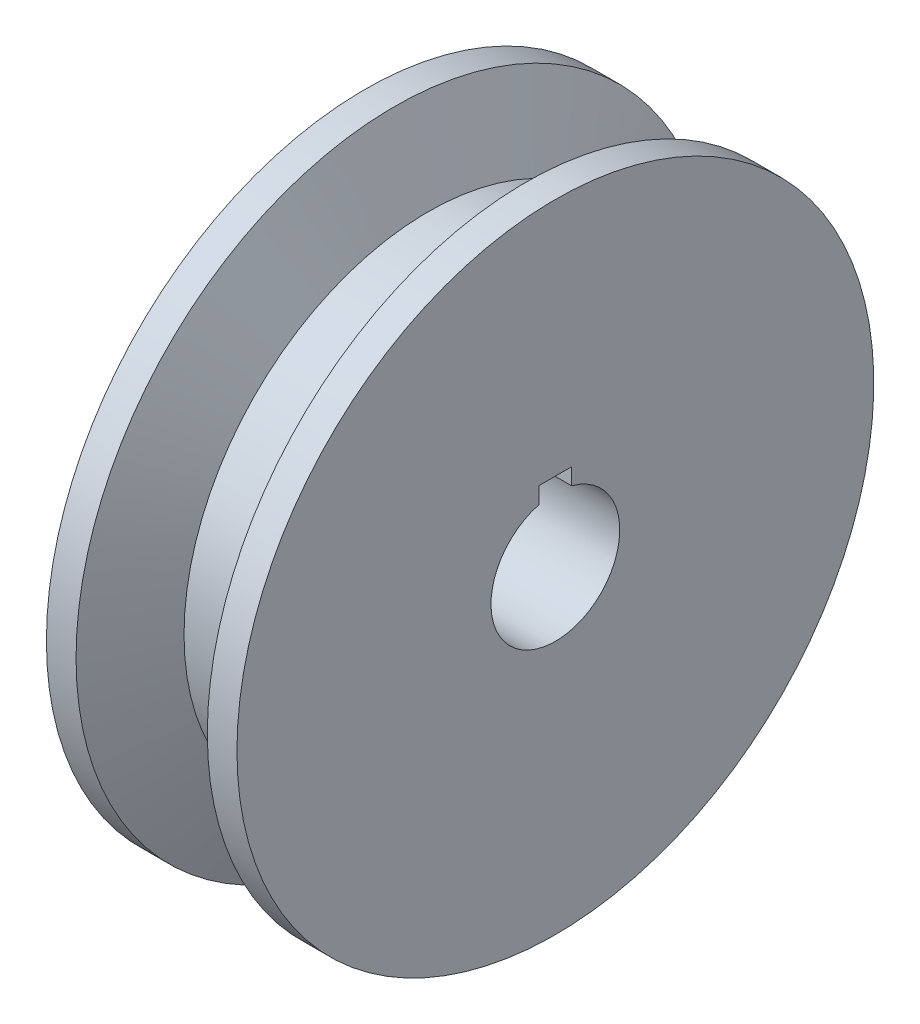
SolidWorks part; units mm, degrees
material "Brass"
ref_plane "Front Plane" through (0, 0, 0) normal (0, 0, 1) x (1, 0, 0)
ref_plane "Top Plane" through (0, 0, 0) normal (0, 1, 0) x (1, 0, 0)
ref_plane "Right Plane" through (0, 0, 0) normal (1, 0, 0) x (0, 0, -1)
sketch "Sketch1" plane through (0, 0, 0) normal (0, 0, 1) x (1, 0, 0)
  line L0 (0, 0) -> (31.75, 0) construction
  line L1 (31.75, 9.652) -> (0, 9.652)
  line L2 (0, 9.652) -> (0, 15.875)
  line L3 (0, 15.875) -> (3.175, 15.875)
  line L4 (3.175, 15.875) -> (3.175, 47.752)
  line L5 (3.175, 47.752) -> (7.62, 47.752)
  line L6 (7.62, 47.752) -> (12.7, 36.6395)
  line L7 (12.7, 36.6395) -> (22.225, 36.6395)
  line L8 (22.225, 36.6395) -> (27.305, 47.752)
  line L9 (27.305, 47.752) -> (31.75, 47.752)
  line L10 (31.75, 47.752) -> (31.75, 9.652)
  dimension "D1" = 9.652
  dimension "D2" = 3.175
  dimension "D3" = 15.875
  dimension "D4" = 9.525
  dimension "D5" = 28.575
  dimension "D6" = 9.525
  dimension "D7" = 4.445
  dimension "D8" = 38.1
  dimension "D9" = 26.9875
revolve "Revolve1" add sketch "Sketch1" angle 360 about L0
sketch "Sketch2" plane through (0, 0, 0) normal (-1, 0, 0) x (0, 0, 1)
  line L0 (-2.4384, 9.3389) -> (-2.4384, 11.811)
  line L1 (-2.4384, 11.811) -> (2.4384, 11.811)
  line L2 (2.4384, 11.811) -> (2.4384, 9.3389)
  circle A0 centre (0, 0) radius 9.652 construction
  arc A1 (2.4384, 9.3389) -> (-2.4384, 9.3389) centre (0, 0) ccw
  point P5 (0, 11.811)
  dimension "D1" = 11.811
  dimension "D2" = 4.8768
extrude "Cut-Extrude1" cut sketch "Sketch2" against normal up to next
